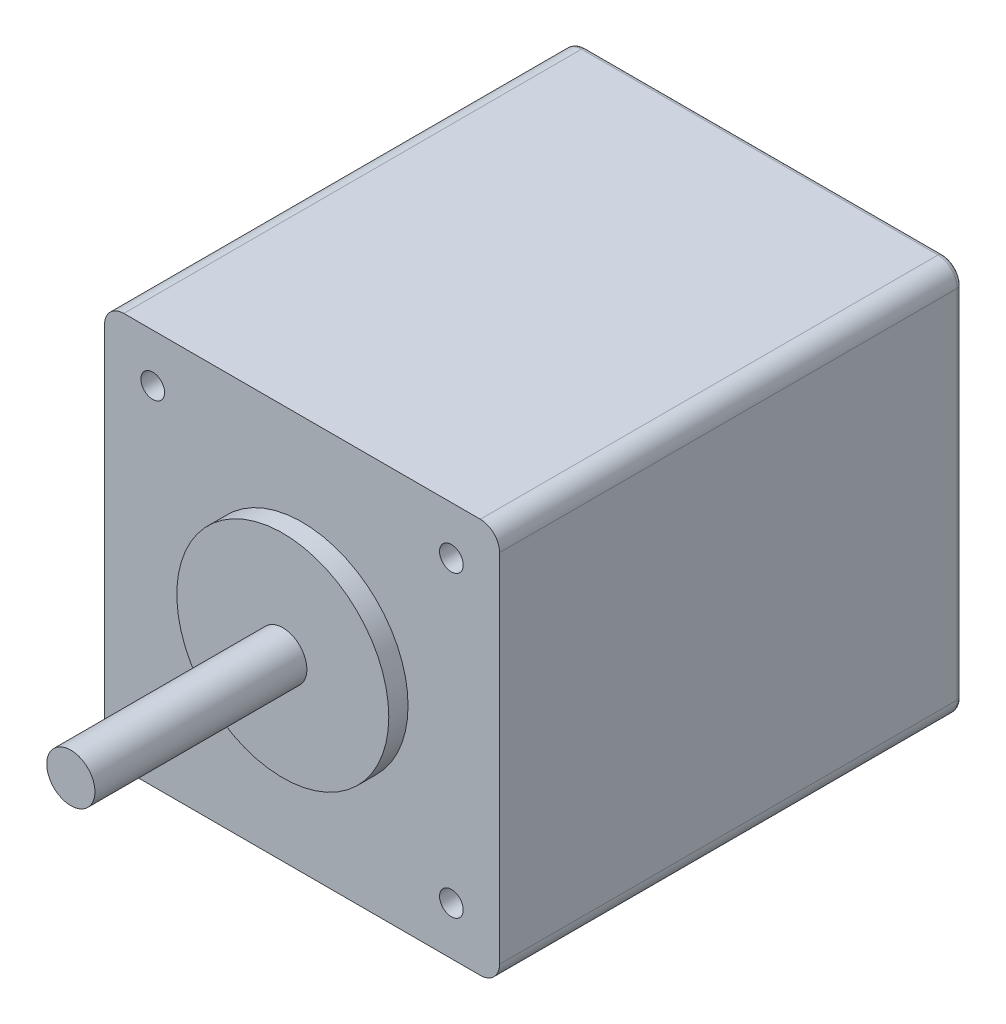
SolidWorks part; units mm, degrees
ref_plane "Front Plane" through (0, 0, 0) normal (0, 0, 1) x (1, 0, 0)
ref_plane "Top Plane" through (0, 0, 0) normal (0, 1, 0) x (1, 0, 0)
ref_plane "Right Plane" through (0, 0, 0) normal (1, 0, 0) x (0, 0, -1)
ref_plane "Plane1" through (0, 41, 0) normal (0, 1, 0) x (1, 0, 0)
sketch "Sketch1" plane through (0, 41, 0) normal (0, 1, 0) x (1, 0, 0)
  line L0 (-41, -48) -> (0, -48)
  line L1 (0, -48) -> (0, 0)
  line L2 (0, 0) -> (-41, 0)
  line L3 (-41, 0) -> (-41, -48)
extrude "Boss-Extrude1" add sketch "Sketch1" against normal blind 41
ref_plane "Plane2" through (0, 20.5, 0) normal (0, 1, 0) x (1, 0, 0)
sketch "Sketch2" plane through (0, 20.5, 0) normal (0, 1, 0) x (1, 0, 0)
  line L0 (-9.5, -48) -> (-20.5, -48)
  line L1 (-20.5, -48) -> (-20.5, -72)
  line L2 (-20.5, -72) -> (-18, -72)
  line L3 (-18, -72) -> (-18, -50)
  line L4 (-18, -50) -> (-9.5, -50)
  line L5 (-9.5, -50) -> (-9.5, -48)
  line L6 (-20.5, -48) -> (-20.5, -72) construction
revolve "Revolve1" add sketch "Sketch2" angle 360 about L6
hole_wizard "M2 Clearance Hole1" positions "Sketch4" profile "Sketch3" hole size "M2" standard "ANSI Metric"
sketch "Sketch4" plane through (0, 0, 48) normal (0, 0, 1) x (1, 0, 0)
  point P0 (-36.0003, 4.9997)
  point P1 (-5.0001, 5.0001)
  point P2 (-4.9996, 36.0004)
  point P3 (-35.9994, 35.9994)
sketch "Sketch3" plane through (-36.0003, 4.9997, 48) normal (1, 0, 0) x (0, -1, 0)
  line L0 (0, 0) -> (0, 4.5)
  line L1 (0, 4.5) -> (1.2295, 4.5)
  line L2 (1.2295, 4.5) -> (1.2295, 0)
  line L5 (1.2295, 0) -> (0, 0)
  line L10 (0, 4.5) -> (-1.2295, 4.5) construction
  line L11 (0, -6.35) -> (0, 107.95) construction
  dimension "Hole Dia." = 2.459
  dimension "Hole Depth" = 4.5
  dimension "Drill Angle" = 180
fillet "Fillet1" radius 2 4 edges at (-41, 41, 24) (0, 41, 24) (-41, 0, 24) (0, 0, 24)
fillet "Fillet2" radius 0.5 8 edges at (-0.5858, 0.5858, 0) (-20.5, 0, 0) (0, 20.5, 0) (-40.4142, 0.5858, 0) (-0.5858, 40.4142, 0) (-41, 20.5, 0) (-20.5, 41, 0) (-40.4142, 40.4142, 0)
